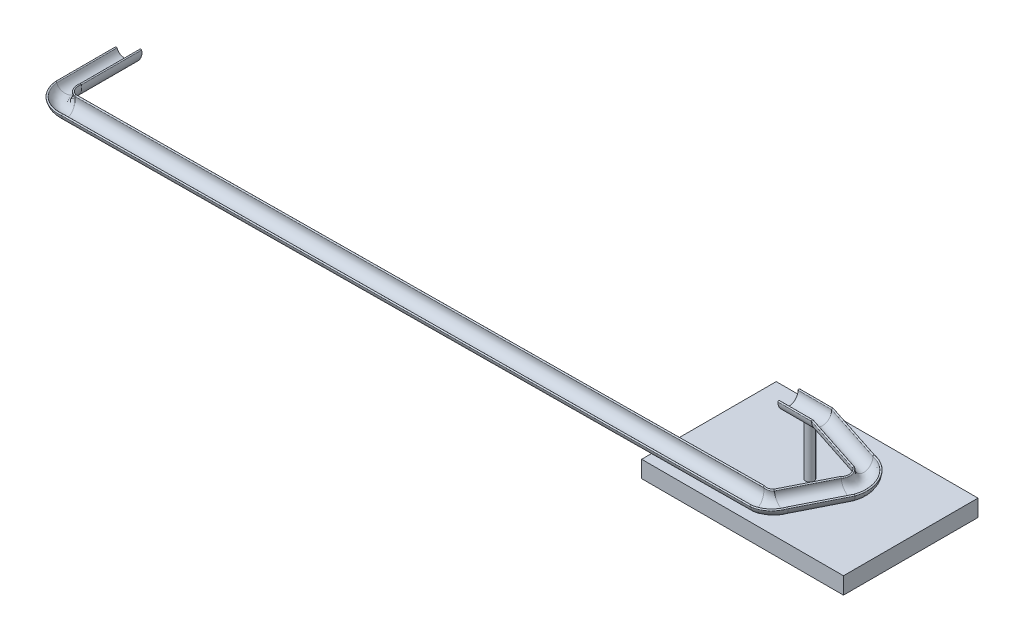
SolidWorks part; units mm, degrees
ref_plane "前基準面" through (0, 0, 0) normal (0, 0, 1) x (1, 0, 0)
ref_plane "上基準面" through (0, 0, 0) normal (0, 1, 0) x (1, 0, 0)
ref_plane "右基準面" through (0, 0, 0) normal (1, 0, 0) x (0, 0, -1)
sketch "草圖1" plane through (0, 0, 0) normal (0, 1, 0) x (1, 0, 0)
  line L1 (60, -40) -> (-60, -40)
  line L2 (60, -40) -> (60, 40)
  line L3 (60, 40) -> (-60, 40)
  line L4 (-60, -40) -> (-60, 40)
  line L5 (60, -40) -> (-60, 40) construction
  line L6 (60, 40) -> (-60, -40) construction
  point P1 (0, 0)
  dimension "D1" = 80
  dimension "D2" = 120
extrude "填料-伸長1" add sketch "草圖1" along normal blind 10
sketch "草圖2" plane through (0, 10, 0) normal (0, 1, 0) x (1, 0, 0)
  circle A0 centre (0, 0) radius 2.5
  dimension "D1" = 5
extrude "填料-伸長2" add sketch "草圖2" along normal blind 30
sketch "草圖3" plane through (0, 0, 0) normal (0, 0, 1) x (1, 0, 0)
  line L0 (-12.5, 41) -> (7.5, 41)
  line L1 (2.5, 40) -> (-2.5, 40) construction
  line L2 (-2.5, 40) -> (-2.5, 10) construction
  point P6 (0, 0)
  dimension "D1" = 1
  dimension "D2" = 10
  dimension "D3" = 20
ref_plane "平面1" through (-12.5, 0, 0) normal (1, 0, 0) x (0, 0, -1)
sketch "草圖4" plane through (-12.5, 0, 0) normal (1, 0, 0) x (0, 0, -1)
  arc A0 (-5.5, 46.5) -> (5.5, 46.5) centre (0, 46.5) ccw
  arc A1 (-6.5, 46.5) -> (6.5, 46.5) centre (0, 46.5) ccw
  arc A2 (6.5, 46.5) -> (5.5, 46.5) centre (6, 46.5) ccw
  arc A3 (-5.5, 46.5) -> (-6.5, 46.5) centre (-6, 46.5) ccw
  point P0 (0, 41)
  dimension "D1" = 13
  dimension "D2" = 11
sweep "掃出1" add profiles "草圖4" path "草圖3"
sketch3d "3D草圖1"
  line L0 (7.5, 41, 0) -> (42.4018, 39.5639, 10.3691)
  line L1 (47.8817, 37.8637, 25.3516) -> (32.0698, 35.3583, 49.2333)
  line L2 (23.7262, 34.8457, 53.7048) -> (-385.8772, 31.5355, 53.7048)
  line L4 (-395.8769, 31.4547, 43.7048) -> (-395.8769, 31.4547, 7.9231)
  arc A0 (32.0698, 35.3583, 49.2333) -> (23.7262, 34.8457, 53.7048) centre (23.7182, 35.8363, 43.7539) ccw
  arc A1 (42.4018, 39.5639, 10.3691) -> (47.8817, 37.8637, 25.3516) centre (39.5302, 38.5362, 19.8926) ccw
  arc A2 (-385.8772, 31.5355, 53.7048) -> (-395.8769, 31.4547, 43.7048) centre (-385.8772, 31.5355, 43.7048) ccw
  point P7 (29.1093, 34.8892, 53.7048)
  point P8 (23.7986, 25.8858, 42.7633)
  point P11 (34.5031, 41, 0)
  point P12 (39.4473, 28.5969, 18.795)
  point P15 (-395.8769, 31.4547, 53.7048)
  point P16 (-385.7964, 21.5358, 43.7048)
  dimension "D1" = 10
  dimension "D3" = 10
  dimension "D2" = 425
sketch "草圖5" plane through (7.5, 0, 0) normal (1, 0, 0) x (0, 0, -1)
  arc A0 (-5.5, 46.5) -> (5.5, 46.5) centre (0, 46.5) ccw
  arc A1 (-6.5, 46.5) -> (6.5, 46.5) centre (0, 46.5) ccw
  arc A2 (6.5, 46.5) -> (5.5, 46.5) centre (6, 46.5) ccw
  arc A3 (-5.5, 46.5) -> (-6.5, 46.5) centre (-6, 46.5) ccw
  point P0 (0, 41)
  dimension "D1" = 13
  dimension "D2" = 11
sweep "掃出2" add profiles "草圖5" path "3D草圖1"
